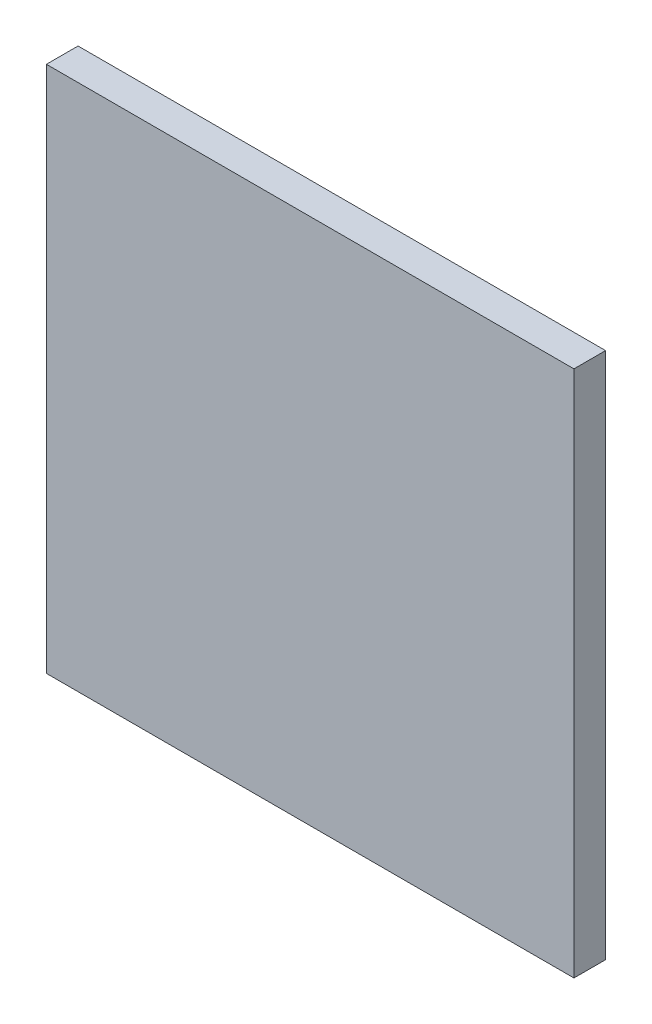
SolidWorks part; units mm, degrees
ref_plane "前视基准面" through (0, 0, 0) normal (0, 0, 1) x (1, 0, 0)
ref_plane "上视基准面" through (0, 0, 0) normal (0, 1, 0) x (1, 0, 0)
ref_plane "右视基准面" through (0, 0, 0) normal (1, 0, 0) x (0, 0, -1)
other "Configuration Table"
sketch "草图1" plane through (0, 0, 0) normal (0, 0, 1) x (1, 0, 0)
  line L1 (0, 0) -> (50, 0)
  line L2 (0, 0) -> (0, 50)
  line L3 (0, 50) -> (50, 50)
  line L4 (50, 0) -> (50, 50)
  dimension "D1" = 50
  dimension "D2" = 50
extrude "凸台-拉伸1" add sketch "草图1" along normal blind 3
sketch "草图2" plane through (0, 0, 3) normal (0, 0, 1) x (1, 0, 0)
  line L0 (50, 50) -> (0, 50) construction
  line L1 (0, 50) -> (0, 0) construction
  circle A0 centre (25, 25) radius 6
  dimension "D1" = 12
  dimension "D2" = 25
  dimension "D3" = 25
